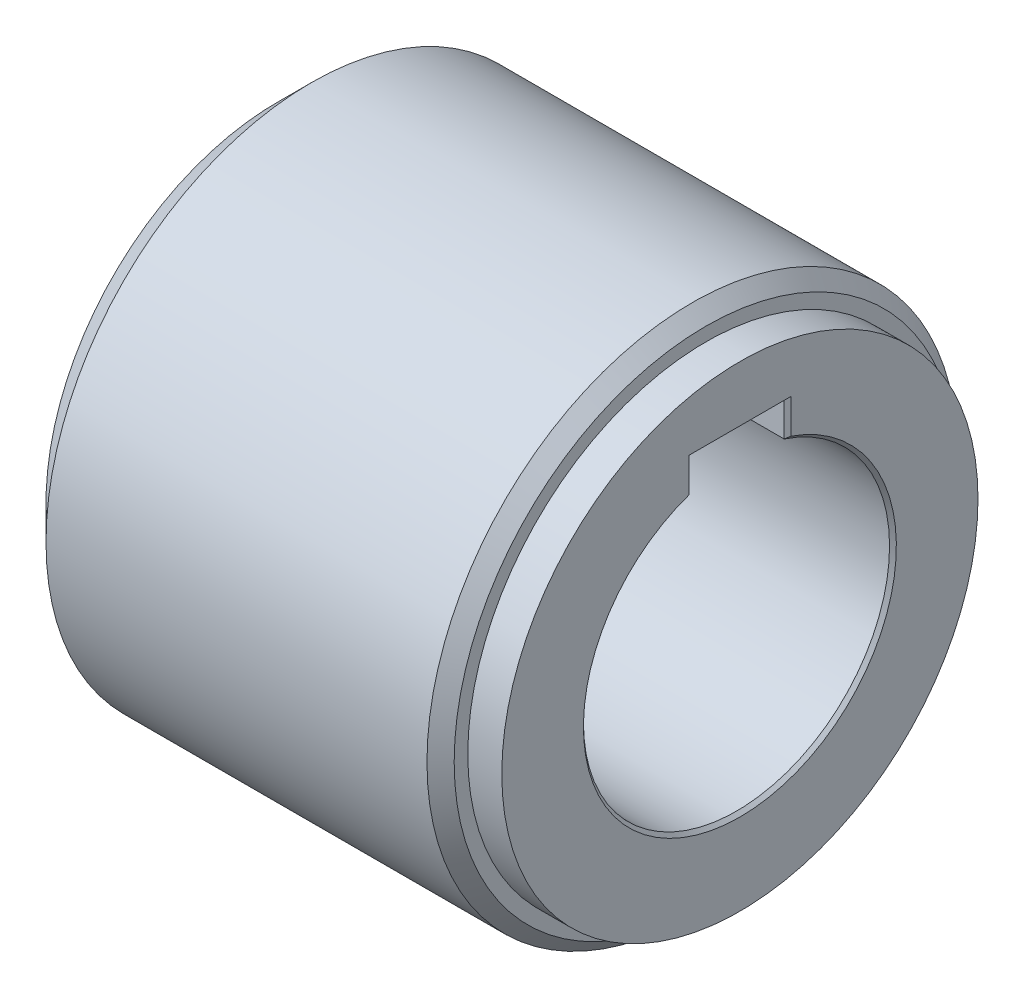
SolidWorks part; units mm, degrees
material "AISI 304"
ref_plane "Спереди" through (0, 0, 0) normal (0, 0, 1) x (1, 0, 0)
ref_plane "Сверху" through (0, 0, 0) normal (0, 1, 0) x (1, 0, 0)
ref_plane "Справа" through (0, 0, 0) normal (1, 0, 0) x (0, 0, -1)
other "Configuration Table"
sketch "Эскиз1" plane through (0, 0, 0) normal (1, 0, 0) x (0, 0, -1)
  line L0 (0, 0) -> (0, 26.3) construction
  line L1 (-7, 26.3) -> (7, 26.3)
  line L2 (7, 26.3) -> (7, 21.3834)
  line L3 (-7, 26.3) -> (-7, 21.3834)
  arc A0 (-7, 21.3834) -> (7, 21.3834) centre (0, 0) ccw
  circle A1 centre (0, 0) radius 39
  point P8 (0, 26.3)
  dimension "D1" = 45
  dimension "D4" = 78
  dimension "D2" = 14
  dimension "D3" = 48.8
extrude "Бобышка-Вытянуть1" add sketch "Эскиз1" along normal mid plane 68
chamfer "Фаска1" distance 5 angle 45 1 edges at (-34, 0, -39)
chamfer "Фаска2" distance 0.5 angle 45 8 edges at (34, 23.8417, -7) (34, 26.3, 0) (34, 23.8417, 7) (34, -22.5, 0) (-34, 23.8417, 7) (-34, 26.3, 0) (-34, 23.8417, -7) (-34, -22.5, 0)
sketch "Эскиз2" plane through (0, 0, 0) normal (0, 0, 1) x (1, 0, 0)
  line L0 (0, 0) -> (34.1651, 0) construction
  line L1 (50, 0) -> (-50, 0) construction
  line L2 (34, 35) -> (29, 35)
  line L3 (34, -39) -> (34, 39) construction
  line L4 (29, 35) -> (29, 37)
  line L5 (29, 37) -> (27, 39)
  line L6 (34, 39) -> (-29, 39) construction
  line L7 (27, 39) -> (34, 39)
  line L8 (34, 39) -> (34, 35)
  dimension "D1" = 45
  dimension "D2" = 2
  dimension "D3" = 5
  dimension "D4" = 70
revolve "Вырез-Повернуть1" cut sketch "Эскиз2" angle 360 about L0
